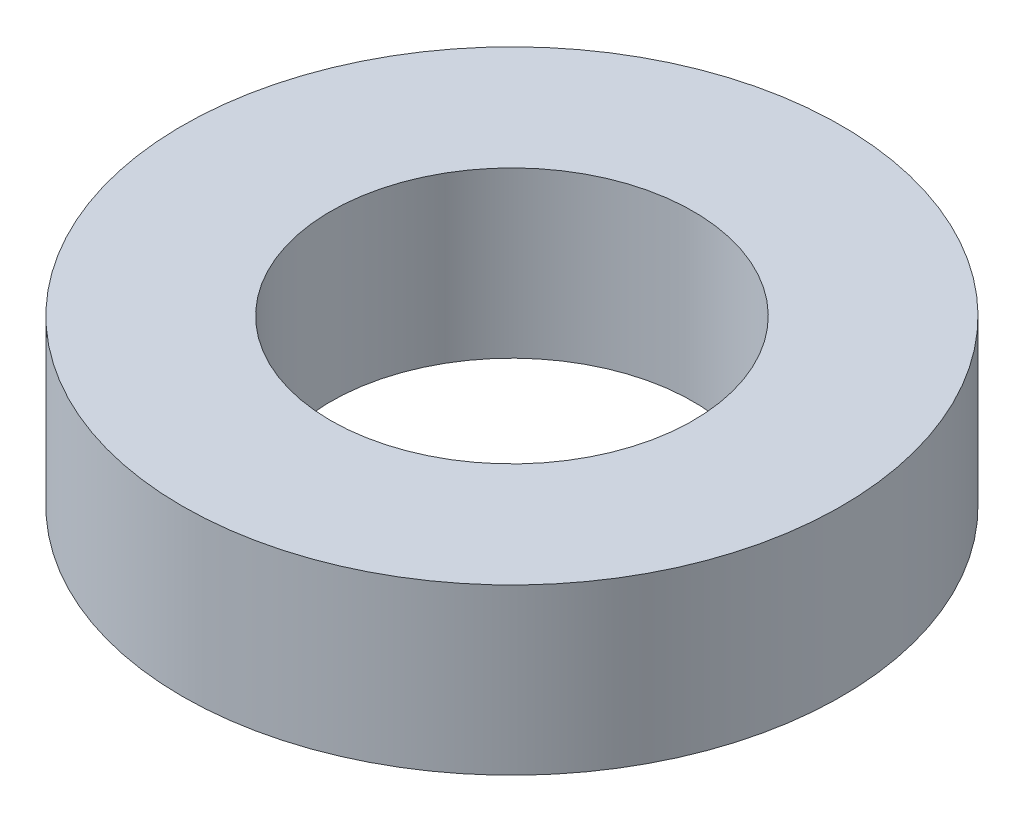
SolidWorks part; units mm, degrees
ref_plane "Front Plane" through (0, 0, 0) normal (0, 0, 1) x (1, 0, 0)
ref_plane "Top Plane" through (0, 0, 0) normal (0, 1, 0) x (1, 0, 0)
ref_plane "Right Plane" through (0, 0, 0) normal (1, 0, 0) x (0, 0, -1)
sketch "Sketch1" plane through (0, 0, 0) normal (0, 1, 0) x (1, 0, 0)
  circle A0 centre (0, 0) radius 1.1
  circle A1 centre (0, 0) radius 2
  dimension "D1" = 2.2
  dimension "D2" = 4
extrude "Boss-Extrude1" add sketch "Sketch1" along normal mid plane 1
